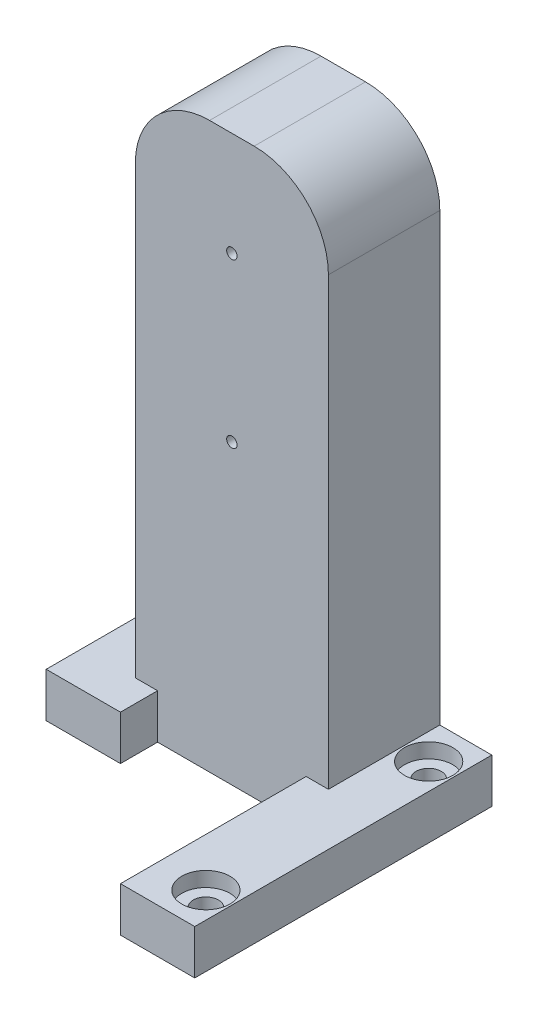
SolidWorks part; units mm, degrees
ref_plane "Plan de face" through (0, 0, 0) normal (0, 0, 1) x (1, 0, 0)
ref_plane "Plan de dessus" through (0, 0, 0) normal (0, 1, 0) x (1, 0, 0)
ref_plane "Plan de droite" through (0, 0, 0) normal (1, 0, 0) x (0, 0, -1)
sketch "Esquisse1" plane through (0, 0, 0) normal (0, 0, 1) x (1, 0, 0)
  line L0 (0, 0) -> (-20, 0)
  line L1 (-20, 0) -> (20, 0) construction
  line L2 (-20, 0) -> (-20, 76) construction
  line L3 (-20, 76) -> (20, 76) construction
  line L4 (20, 0) -> (20, 76) construction
  line L5 (-20, 0) -> (-20, 6)
  line L6 (-20, 6) -> (-13, 6)
  line L7 (-13, 6) -> (-13, 76)
  line L8 (-13, 76) -> (13, 76)
  line L9 (13, 76) -> (13, 6)
  line L10 (13, 6) -> (20, 6)
  line L11 (20, 6) -> (20, 0)
  line L12 (20, 0) -> (0, 0)
  point P4 (0, 0)
  dimension "D1" = 26
  dimension "D2" = 70
  dimension "D3" = 7
  dimension "D4" = 7
  dimension "D5" = 6
  dimension "D6" = 6
extrude "Boss.-Extru.1" add sketch "Esquisse1" along normal blind 15
sketch "Esquisse2" plane through (0, 0, 0) normal (0, -1, 0) x (1, 0, 0)
  line L1 (-20, 15) -> (20, 15) construction
  line L2 (-20, 15) -> (-20, 40) construction
  line L3 (-20, 40) -> (20, 40) construction
  line L4 (20, 15) -> (20, 40) construction
  line L9 (20, 40) -> (10, 40)
  line L10 (20, 40) -> (20, 15)
  line L11 (20, 15) -> (10, 15)
  line L12 (10, 40) -> (10, 15)
  line L13 (-20, 15) -> (-10, 15)
  line L14 (-20, 15) -> (-20, 20)
  line L15 (-20, 20) -> (-10, 20)
  line L16 (-10, 15) -> (-10, 20)
  dimension "D1" = 25
  dimension "D2" = 40
  dimension "D3" = 10
  dimension "D4" = 10
  dimension "D5" = 5
extrude "Boss.-Extru.2" add sketch "Esquisse2" against normal blind 6
sketch "Esquisse3" plane through (0, 0, 15) normal (0, 0, 1) x (1, 0, 0)
  line L0 (0, 76) -> (0, 0) construction
  line L1 (13, 76) -> (-13, 76) construction
  line L2 (-10, 0) -> (10, 0) construction
  circle A0 centre (0, 62) radius 1
  circle A1 centre (0, 40) radius 1
  dimension "D1" = 2
  dimension "D2" = 2
  dimension "D3" = 22
  dimension "D4" = 40
sketch "Esquisse4" plane through (0, 6, 0) normal (0, 1, 0) x (1, 0, 0)
  line L0 (-16.5, 0) -> (-16.5, -20) construction
  line L1 (-13, 0) -> (-20, 0) construction
  line L2 (16.5, 0) -> (16.5, -40) construction
  line L3 (20, 0) -> (13, 0) construction
  line L5 (20, -40) -> (10, -40) construction
  line L6 (-10, -20) -> (-20, -20) construction
  circle A0 centre (-16.5, -5) radius 1
  circle A1 centre (16.5, -5) radius 1
  circle A2 centre (16.5, -35) radius 1
  point P9 (-16.5, -25)
  point P19 (-16.5, -40)
  dimension "D1" = 2
  dimension "D2" = 2
  dimension "D3" = 2
  dimension "D5" = 5
  dimension "D6" = 5
  dimension "D8" = 5
hole_wizard "Dégagement M1.21" positions "Esquisse5" profile "Esquisse7" hole size "M1.2" standard "ISO" end condition through all
sketch "Esquisse5" plane through (0, 0, 15) normal (0, 0, 1) x (1, 0, 0)
  point P0 (0, 62)
  point P3 (0, 40)
sketch "Esquisse7" plane through (0, 62, 15) normal (1, 0, 0) x (0, -1, 0)
  line L0 (0, 0) -> (0, 15)
  line L1 (0, 15) -> (0.7, 15)
  line L2 (0.7, 15) -> (0.7, 0)
  line L5 (0.7, 0) -> (0, 0)
  line L11 (0, -6.35) -> (0, 107.95) construction
  dimension "Diamètre du perçage jusqu'au prochain" = 1.4
  dimension "Profondeur du perçage jusqu'au prochain" = 15
hole_wizard "Chambrage pour tête cylindrique fendue M31" positions "Esquisse8" profile "Esquisse9" counterbore size "M3" standard "ISO" end condition through all
sketch "Esquisse8" plane through (0, 6, 0) normal (0, 1, 0) x (1, 0, 0)
  point P0 (-16.5, -5)
  point P3 (16.5, -5)
  point P6 (16.5, -35)
  point P12 (0, 0)
sketch "Esquisse9" plane through (-16.5, 6, 5) normal (1, 0, 0) x (0, 0, 1)
  line L0 (0, 0) -> (0, 6)
  line L1 (0, 6) -> (1.7, 6)
  line L3 (1.7, 6) -> (1.7, 2)
  line L4 (1.7, 2) -> (3.25, 2)
  line L5 (3.25, 2) -> (3.25, 0)
  line L7 (3.25, 0) -> (0, 0)
  line L11 (0, -6.35) -> (0, 107.95) construction
  dimension "Diamètre du perçage jusqu'au prochain" = 3.4
  dimension "Profondeur du perçage jusqu'au prochain" = 6
  dimension "Diamètre du chambrage" = 6.5
  dimension "Profondeur du chambrage" = 2
fillet "Congé1" radius 10 2 edges at (13, 76, 7.5) (-13, 76, 7.5)
equation "\"hauteur\"= 40'hauteur vis du bas"
equation "\"D4@Esquisse3\"=\"hauteur\""
